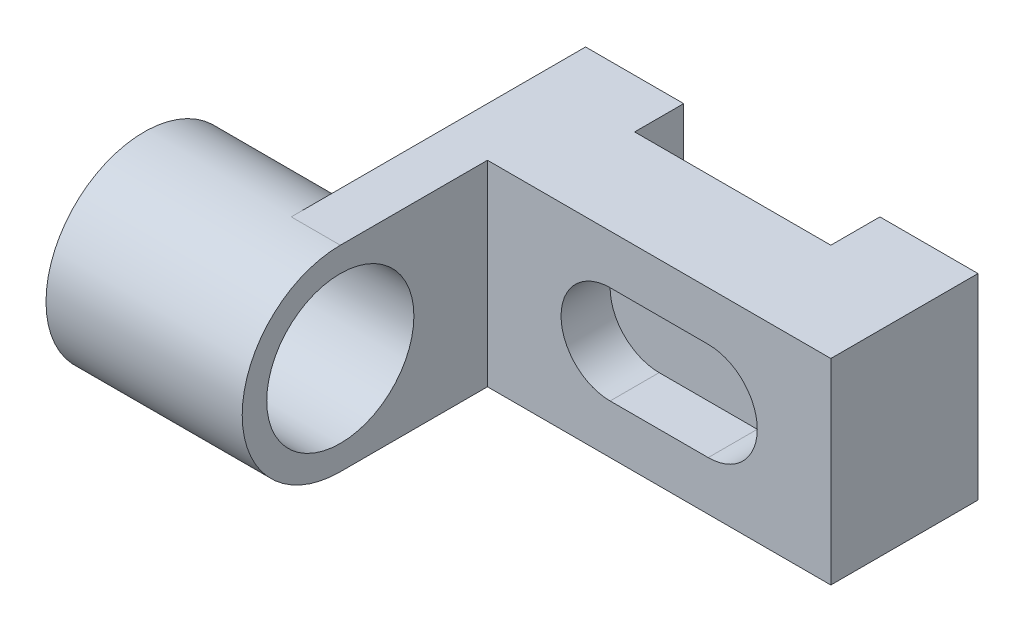
SolidWorks part; units mm, degrees
ref_plane "前基準面" through (0, 0, 0) normal (0, 0, 1) x (1, 0, 0)
ref_plane "上基準面" through (0, 0, 0) normal (0, 1, 0) x (1, 0, 0)
ref_plane "右基準面" through (0, 0, 0) normal (1, 0, 0) x (0, 0, -1)
sketch "草圖1" plane through (0, 0, 0) normal (0, 0, 1) x (1, 0, 0)
  line L1 (40, 20) -> (-40, 20)
  line L2 (40, 20) -> (40, -20)
  line L3 (40, -20) -> (-40, -20)
  line L4 (-40, 20) -> (-40, -20)
  line L5 (40, 20) -> (-40, -20) construction
  line L6 (40, -20) -> (-40, 20) construction
  point P0 (0, 0)
  point P16 (0, 0)
  dimension "D1" = 80
  dimension "D2" = 40
extrude "填料-伸長1" add sketch "草圖1" along normal blind 30 contours L1 L4 L3 L2
sketch "草圖2" plane through (0, -20, 0) normal (0, -1, 0) x (1, 0, 0)
  line L0 (40, 0) -> (-40, 0) construction
  line L1 (20, 10) -> (-20, 10)
  line L2 (20, 10) -> (20, -3.1476)
  line L3 (20, -3.1476) -> (-20, -3.1476)
  line L4 (-20, 10) -> (-20, -3.1476)
  line L5 (20, 10) -> (-20, -3.1476) construction
  line L6 (20, -3.1476) -> (-20, 10) construction
  line L7 (40, 30) -> (40, 0) construction
  dimension "D1" = 10
  dimension "D2" = 40
  dimension "D3" = 20
extrude "除料-伸長1" cut sketch "草圖2" against normal through all
sketch "草圖3" plane through (0, 0, 30) normal (0, 0, 1) x (1, 0, 0)
  line L0 (15, 0) -> (-5, 0) construction
  line L1 (15, -10) -> (-5, -10)
  line L2 (15, 10) -> (-5, 10)
  line L3 (40, 20) -> (40, -20) construction
  line L4 (0, 0) -> (-21.4913, 0) construction
  arc A0 (15, -10) -> (15, 10) centre (15, 0) ccw
  arc A1 (-5, 10) -> (-5, -10) centre (-5, 0) ccw
  point P2 (5, 0)
  dimension "D1" = 20
  dimension "D2" = 20
  dimension "D3" = 25
extrude "除料-伸長2" cut sketch "草圖3" against normal blind 10
sketch "草圖5" plane through (-40, 0, 0) normal (-1, 0, 0) x (0, 0, 1)
  line L1 (30, -20) -> (60, -20)
  line L2 (30, -20) -> (30, 20)
  line L3 (30, 20) -> (60, 20)
  arc A0 (60, -20) -> (60, 20) centre (60, 0) ccw
  circle A1 centre (60, 0) radius 15
  dimension "D1" = 30
  dimension "D2" = 30
extrude "填料-伸長2" add sketch "草圖5" against normal blind 10
sketch "草圖6" plane through (-40, 0, 0) normal (-1, 0, 0) x (0, 0, 1)
  circle A0 centre (60, 0) radius 20
  circle A1 centre (60, 0) radius 15
extrude "填料-伸長3" add sketch "草圖6" along normal blind 30
